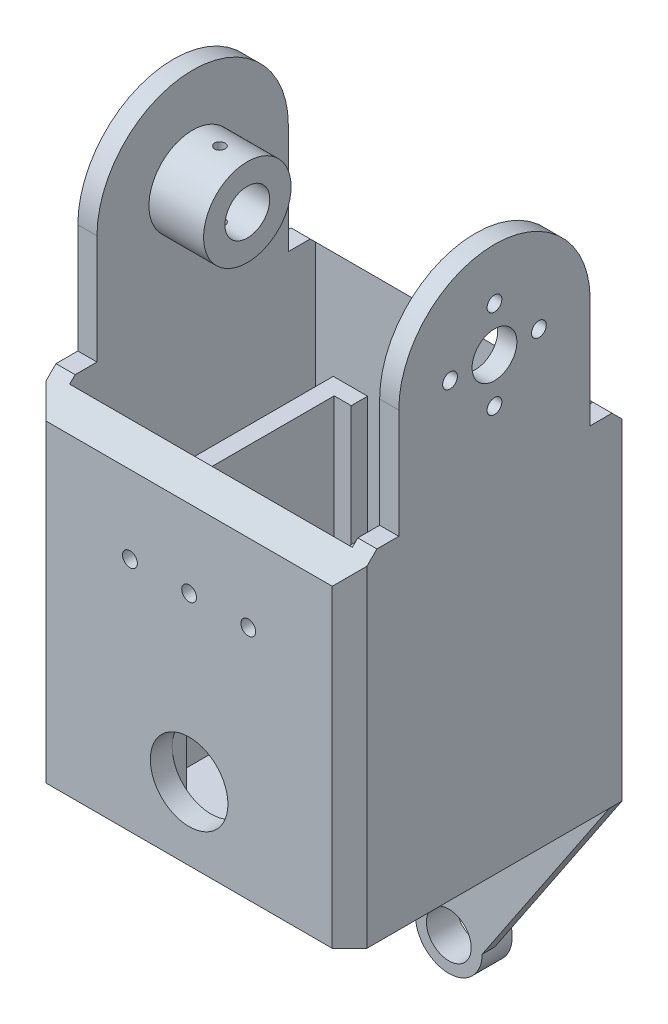
SolidWorks part; units mm, degrees
material "PLA"
ref_plane "Front Plane" through (0, 0, 0) normal (0, 0, 1) x (1, 0, 0)
ref_plane "Top Plane" through (0, 0, 0) normal (0, 1, 0) x (1, 0, 0)
ref_plane "Right Plane" through (0, 0, 0) normal (1, 0, 0) x (0, 0, -1)
sketch "Sketch1" plane through (0, 0, 0) normal (1, 0, 0) x (0, 0, -1)
  line L0 (-17.5, 0) -> (-17.5, -20)
  line L1 (17.5, 0) -> (17.5, -20)
  line L2 (17.5, -20) -> (22.5, -20)
  line L3 (-17.5, -20) -> (-22.5, -20)
  line L4 (22.5, -20) -> (22.5, -76)
  line L5 (-22.5, -20) -> (-22.5, -76)
  line L6 (22.5, -76) -> (-22.5, -76)
  arc A0 (17.5, 0) -> (-17.5, 0) centre (0, 0) ccw
  circle A1 centre (0, 0) radius 4.1
  dimension "D1" = 35
  dimension "D7" = 8.2
  dimension "D2" = 20
  dimension "D3" = 5
  dimension "D4" = 5
  dimension "D5" = 56
  dimension "D6" = 56
extrude "Boss-Extrude1" add sketch "Sketch1" against normal blind 3.5
sketch "Sketch2" plane through (0, 0, 0) normal (1, 0, 0) x (0, 0, -1)
  line L7 (-17.5, 0) -> (-17.5, -20)
  line L8 (-17.5, -20) -> (-22.5, -20)
  line L9 (-22.5, -20) -> (-22.5, -76)
  line L10 (-22.5, -76) -> (22.5, -76)
  line L11 (22.5, -76) -> (22.5, -20)
  line L12 (22.5, -20) -> (17.5, -20)
  line L13 (17.5, -20) -> (17.5, 0)
  line L16 (-22.5, -20) -> (-22.5, -76)
  line L17 (-22.5, -76) -> (22.5, -76)
  line L18 (22.5, -76) -> (22.5, -20)
  line L28 (-22.5, -20) -> (-26.5, -20)
  line L29 (-26.5, -20) -> (-26.5, -79.175)
  line L30 (22.5, -20) -> (26.5, -20)
  line L31 (26.5, -20) -> (26.5, -79.175)
  line L45 (-26.5, -79.175) -> (26.5, -79.175)
  arc A1 (17.5, 0) -> (-17.5, 0) centre (0, 0) ccw
  dimension "D2" = 4
  dimension "D3" = 4
  dimension "D1" = 0
extrude "Boss-Extrude2" add sketch "Sketch2" along normal blind 51.7 and the other way blind 3.5
chamfer "Chamfer2" distance 5 angle 45 2 edges at (24.1, -20, -26.5) (24.1, -20, 26.5)
sketch "Sketch4" plane through (0, -76, 0) normal (0, 1, 0) x (1, 0, 0)
  line L1 (0, 22.5) -> (51.7, 22.5)
  line L2 (0, 22.5) -> (0, -22.5)
  line L3 (0, -22.5) -> (51.7, -22.5)
  line L4 (51.7, 22.5) -> (51.7, -22.5)
extrude "Cut-Extrude1" cut sketch "Sketch4" against normal up to next
sketch "Sketch5" plane through (51.7, 0, 0) normal (1, 0, 0) x (0, 0, -1)
  line L9 (21.5, -20) -> (17.5, -20)
  line L10 (26.5, -25) -> (21.5, -20)
  line L11 (26.5, -79.175) -> (26.5, -25)
  line L12 (-26.5, -79.175) -> (26.5, -79.175)
  line L13 (-26.5, -25) -> (-26.5, -79.175)
  line L14 (-21.5, -20) -> (-26.5, -25)
  line L15 (-17.5, -20) -> (-21.5, -20)
  line L16 (-17.5, 0) -> (-17.5, -20)
  line L17 (17.5, -20) -> (17.5, 0)
  line L18 (21.5, -20) -> (17.5, -20)
  line L19 (26.5, -25) -> (21.5, -20)
  line L20 (26.5, -79.175) -> (26.5, -25)
  line L21 (-26.5, -79.175) -> (26.5, -79.175)
  line L22 (-26.5, -25) -> (-26.5, -79.175)
  line L23 (-21.5, -20) -> (-26.5, -25)
  line L24 (-17.5, -20) -> (-21.5, -20)
  line L25 (-17.5, 0) -> (-17.5, -20)
  line L26 (17.5, -20) -> (17.5, 0)
  arc A1 (17.5, 0) -> (-17.5, 0) centre (0, 0) ccw
  arc A2 (17.5, 0) -> (-17.5, 0) centre (0, 0) ccw
  circle A4 centre (0, 0) radius 4.1
  dimension "D2" = 8.2
  dimension "D1" = 0
extrude "Boss-Extrude3" add sketch "Sketch5" along normal blind 3.5
sketch "Sketch9" plane through (55.2, 0, 0) normal (1, 0, 0) x (0, 0, -1)
  circle A0 centre (0, 0) radius 8.125 construction
  circle A1 centre (0, 8.125) radius 1.35
  circle A2 centre (8.125, 0) radius 1.35
  circle A3 centre (0, -8.125) radius 1.35
  circle A4 centre (-8.125, 0) radius 1.35
  dimension "D1" = 16.25
  dimension "D2" = 2.7
  dimension "D3" = 2.7
  dimension "D4" = 2.7
  dimension "D5" = 2.7
extrude "Cut-Extrude3" cut sketch "Sketch9" against normal up to next
sketch "Sketch10" plane through (0, -79.175, 0) normal (0, -1, 0) x (1, 0, 0)
  line L2 (0, 22.5) -> (51.7, 22.5)
  line L9 (0, 22.5) -> (0, -22.5)
  line L10 (0, -22.5) -> (51.7, -22.5)
  line L11 (51.7, 22.5) -> (51.7, -22.5)
extrude "Boss-Extrude5" add sketch "Sketch10" along normal blind 3.175
sketch "Sketch26" plane through (0, 0, 26.5) normal (0, 0, 1) x (1, 0, 0)
  line L0 (25.85, -82.35) -> (25.85, -69.065) construction
  line L1 (55.2, -82.35) -> (-3.5, -82.35) construction
  circle A0 centre (25.85, -69.065) radius 7.1
  dimension "D1" = 14.2
extrude "Cut-Extrude6" cut sketch "Sketch26" against normal blind 4
sketch "Sketch27" plane through (0, -79.175, 0) normal (0, 1, 0) x (1, 0, 0)
  line L0 (13.4899, 12.1001) -> (13.4937, -19.3) construction
  line L1 (38.2062, -19.3) -> (38.2062, 12.1001) construction
  line L2 (25.85, -22.5) -> (25.85, 20.6118) construction
  line L3 (0, -22.5) -> (51.7, -22.5) construction
  line L4 (38.4062, -22.5) -> (38.4062, 12.1001)
  line L5 (13.2938, -22.5) -> (13.2938, 12.1001)
  line L6 (13.2938, 12.1001) -> (10.1188, 12.1001)
  line L7 (10.1188, 12.1001) -> (10.1188, -22.5)
  line L8 (10.1188, -22.5) -> (13.2938, -22.5)
  line L9 (38.4062, 12.1001) -> (41.5812, 12.1001)
  line L10 (41.5812, 12.1001) -> (41.5812, -22.5)
  line L11 (41.5812, -22.5) -> (38.4062, -22.5)
  dimension "D1" = 0.2
  dimension "D2" = 3.175
  dimension "D3" = 3.175
extrude "Boss-Extrude6" add sketch "Sketch27" along normal up to surface (45.22 mm away)
sketch "Sketch29" plane through (0, 0, -26.5) normal (0, 0, -1) x (-1, 0, 0)
  line L0 (-25.85, -82.35) -> (-25.85, -117.07) construction
  line L1 (3.5, -82.35) -> (-55.2, -82.35) construction
  line L2 (-55.2, -82.35) -> (-31.95, -117.07)
  line L3 (-19.75, -117.07) -> (3.5, -82.35)
  line L4 (-30.85, -103.5033) -> (-40.9973, -88.35)
  line L5 (3.5, -82.35) -> (-55.2, -82.35) construction
  line L6 (-20.85, -103.5033) -> (-10.7027, -88.35)
  line L7 (-40.9973, -88.35) -> (-40.9973, -82.35)
  line L8 (-10.7027, -88.35) -> (-10.7027, -82.35)
  line L9 (-30.85, -103.5033) -> (-20.85, -103.5033)
  circle A0 centre (-25.85, -117.07) radius 4.1
  circle A1 centre (-25.85, -117.07) radius 6.1
  dimension "D2" = 8.2
  dimension "D3" = 12.2
  dimension "D1" = 34.72
  dimension "D4" = 6
  dimension "D5" = 6
  dimension "D6" = 10
extrude "Boss-Extrude8" add sketch "Sketch29" against normal blind 5.5
chamfer "Chamfer3" distance 3.175 angle 45 6 edges at (-3.5, -53.675, -26.5) (55.2, -53.675, -26.5) (-3.5, -53.675, 26.5) (55.2, -53.675, 26.5) (43.575, -99.71, -26.5) (8.125, -99.71, -26.5)
sketch "Sketch30" plane through (0, 0, 0) normal (1, 0, 0) x (0, 0, -1)
  circle A0 centre (0, 0) radius 4.1
  circle A1 centre (0, 0) radius 8
  dimension "D1" = 8.2
  dimension "D2" = 16
extrude "Boss-Extrude9" add sketch "Sketch30" along normal blind 10
sketch "Sketch31" plane through (0, -20, 0) normal (0, 1, 0) x (1, 0, 0)
  line L0 (5, 8) -> (5, -8) construction
  line L1 (10, 8) -> (0, 8) construction
  line L2 (0, -8) -> (10, -8) construction
  circle A0 centre (5, 0) radius 0.95
  dimension "D1" = 1.9
extrude "Cut-Extrude7" cut sketch "Sketch31" along normal through all
sketch "Sketch32" plane through (0, -79.175, 0) normal (0, 1, 0) x (1, 0, 0)
  line L0 (13.7903, 12.4) -> (13.7903, 12.6) construction
  line L1 (15.4899, 12.4) -> (13.79, 12.4) construction
  line L2 (13.7903, 12.6) -> (16.4, 12.6) construction
  line L3 (16.6, 12.4) -> (16.6, 12.4787) construction
  line L4 (16.4, 12.6) -> (13.2938, 12.6)
  line L5 (13.2938, 12.1001) -> (13.2938, 12.6)
  line L6 (10.1188, 12.1001) -> (10.1188, 15.6001)
  line L7 (16.4, 12.6) -> (16.4, 15.6001)
  line L8 (16.4, 15.6001) -> (10.1188, 15.6001)
  line L9 (10.1188, 12.1001) -> (13.2938, 12.1001)
  line M12 (10.1188, 12.1001) -> (13.2938, 12.1001)
  dimension "D1" = 0.2
  dimension "D2" = 0.2
  dimension "D3" = 3.5
extrude "Boss-Extrude10" add sketch "Sketch32" along normal up to surface (45.22 mm away) contours L7 L8 L6 L5 L4 M12 up to face at (11.7063, -33.955, 5.1999)
sketch "Sketch33" plane through (0, -79.175, 0) normal (0, 1, 0) x (1, 0, 0)
  line L0 (13.1937, -19.6) -> (18.8801, -19.6) construction
  line L1 (13.2938, -22.5) -> (18.6801, -22.5)
  line L2 (13.2938, -22.5) -> (13.2938, -19.8)
  line L3 (13.2938, -19.8) -> (18.6801, -19.8)
  line L4 (18.6801, -22.5) -> (18.6801, -19.8)
  line L5 (13.7937, -19.6) -> (14.9937, -19.6) construction
  line L6 (18.85, -19.6) -> (19.084, -19.6) construction
  line L7 (18.8801, -19.6) -> (18.8801, -21.0143) construction
  dimension "D1" = 0.2
  dimension "D2" = 0.2
extrude "Boss-Extrude11" add sketch "Sketch33" along normal up to surface (45.22 mm away) up to face at (13.2709, -33.955, -1.9001)
ref_plane "Plane1" through (25.85, 0, 0) normal (-1, 0, 0) x (0, 0, 1)
mirror "Mirror1" about plane through (25.85, 0, 0) normal (-1, 0, 0) of "Boss-Extrude11", "Boss-Extrude10"
sketch "Sketch34" plane through (0, -33.955, 0) normal (0, 1, 0) x (1, 0, 0)
  line L0 (13.2938, -19.8) -> (13.2938, 12.6) construction
  line L1 (13.2938, 12.6) -> (16.4, 12.6) construction
  line L2 (16.4, 12.6) -> (16.4, 15.6001) construction
  line L3 (16.4, 15.6001) -> (10.1188, 15.6001) construction
  line L4 (10.1188, 15.6001) -> (10.1188, -22.5) construction
  line L5 (10.1188, -22.5) -> (18.6801, -22.5) construction
  line L6 (18.6801, -22.5) -> (18.6801, -19.8) construction
  line L7 (18.6801, -19.8) -> (13.2938, -19.8) construction
  line L8 (41.5812, -22.5) -> (41.5812, 15.6001) construction
  line L9 (41.5812, 15.6001) -> (35.3, 15.6001) construction
  line L10 (35.3, 15.6001) -> (35.3, 12.6) construction
  line L11 (35.3, 12.6) -> (38.4062, 12.6) construction
  line L12 (38.4062, 12.6) -> (38.4062, -19.8) construction
  line L13 (38.4062, -19.8) -> (33.0199, -19.8) construction
  line L14 (33.0199, -19.8) -> (33.0199, -22.5) construction
  line L15 (33.0199, -22.5) -> (41.5812, -22.5) construction
  line L16 (13.2938, -19.8) -> (13.2938, 12.6)
  line L17 (13.2938, 12.6) -> (16.4, 12.6)
  line L18 (16.4, 12.6) -> (16.4, 15.6001)
  line L19 (16.4, 15.6001) -> (10.1188, 15.6001)
  line L20 (10.1188, 15.6001) -> (10.1188, -22.5)
  line L21 (10.1188, -22.5) -> (18.6801, -22.5)
  line L22 (18.6801, -22.5) -> (18.6801, -19.8)
  line L23 (18.6801, -19.8) -> (13.2938, -19.8)
  line L24 (41.5812, -22.5) -> (41.5812, 15.6001)
  line L25 (41.5812, 15.6001) -> (35.3, 15.6001)
  line L26 (35.3, 15.6001) -> (35.3, 12.6)
  line L27 (35.3, 12.6) -> (38.4062, 12.6)
  line L28 (38.4062, 12.6) -> (38.4062, -19.8)
  line L29 (38.4062, -19.8) -> (33.0199, -19.8)
  line L30 (33.0199, -19.8) -> (33.0199, -22.5)
  line L31 (33.0199, -22.5) -> (41.5812, -22.5)
extrude "Boss-Extrude12" add sketch "Sketch34" along normal blind 0.2
sketch "Sketch35" plane through (0, 0, 26.5) normal (0, 0, 1) x (1, 0, 0)
  circle A0 centre (36.6686, -39.2041) radius 1.35 construction
  circle A1 centre (25.85, -39.2041) radius 1.35 construction
  circle A2 centre (15.0314, -39.2041) radius 1.35 construction
  circle A3 centre (36.6686, -39.2041) radius 1.35
  circle A4 centre (25.85, -39.2041) radius 1.35
  circle A5 centre (15.0314, -39.2041) radius 1.35
extrude "Cut-Extrude8" cut sketch "Sketch35" against normal blind 5
